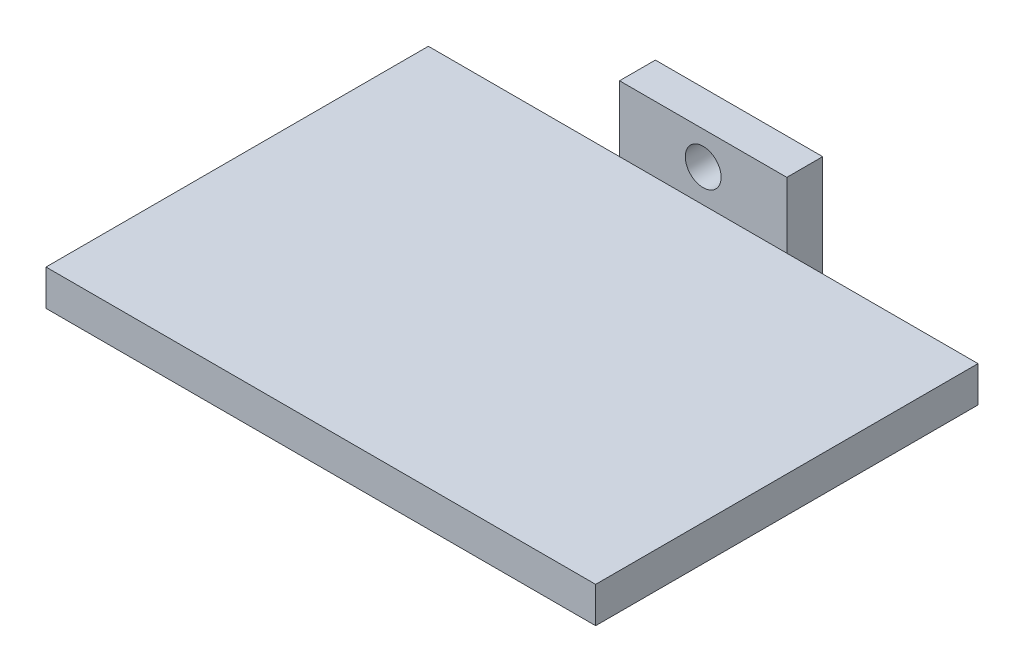
SolidWorks part; units mm, degrees
ref_plane "Front Plane" through (0, 0, 0) normal (0, 0, 1) x (1, 0, 0)
ref_plane "Top Plane" through (0, 0, 0) normal (0, 1, 0) x (1, 0, 0)
ref_plane "Right Plane" through (0, 0, 0) normal (1, 0, 0) x (0, 0, -1)
sketch "Sketch1" plane through (0, 0, 0) normal (0, 0, 1) x (1, 0, 0)
  line L1 (-7, -7) -> (7, -7)
  line L2 (-7, -7) -> (-7, 7)
  line L3 (-7, 7) -> (7, 7)
  line L4 (7, -7) -> (7, 7)
  line L5 (-7, -7) -> (7, 7) construction
  line L6 (-7, 7) -> (7, -7) construction
  point P0 (0, 0)
  dimension "D1" = 14
  dimension "D2" = 14
extrude "Boss-Extrude1" add sketch "Sketch1" along normal blind 3
sketch "Sketch2" plane through (0, 0, 3) normal (0, 0, 1) x (1, 0, 0)
  line L1 (-23, -1.5) -> (23, -1.5)
  line L2 (-23, -1.5) -> (-23, 1.5)
  line L3 (-23, 1.5) -> (23, 1.5)
  line L4 (23, -1.5) -> (23, 1.5)
  line L5 (-23, -1.5) -> (23, 1.5) construction
  line L6 (-23, 1.5) -> (23, -1.5) construction
  point P0 (0, 0)
  dimension "D1" = 3
  dimension "D2" = 46
extrude "Boss-Extrude2" add sketch "Sketch2" along normal blind 32
ref_point "Point1"
ref_point "Point3"
hole_wizard "Ø3.0mm Dowel Hole1" positions "Sketch3" profile "Sketch4" hole size "Ø3.0" standard "ISO" end condition through all
sketch "Sketch3" plane through (0, 0, 3) normal (0, 0, 1) x (1, 0, 0)
  point P0 (0, 4.25)
  point P3 (0, -4.25)
sketch "Sketch4" plane through (0, 4.25, 3) normal (1, 0, 0) x (0, -1, 0)
  line L0 (0, 0) -> (0, 3)
  line L1 (0, 3) -> (1.5, 3)
  line L2 (1.5, 3) -> (1.5, 0)
  line L5 (1.5, 0) -> (0, 0)
  line L11 (0, -6.35) -> (0, 107.95) construction
  dimension "Thru Hole Dia." = 3
  dimension "Thru Hole Depth" = 3
